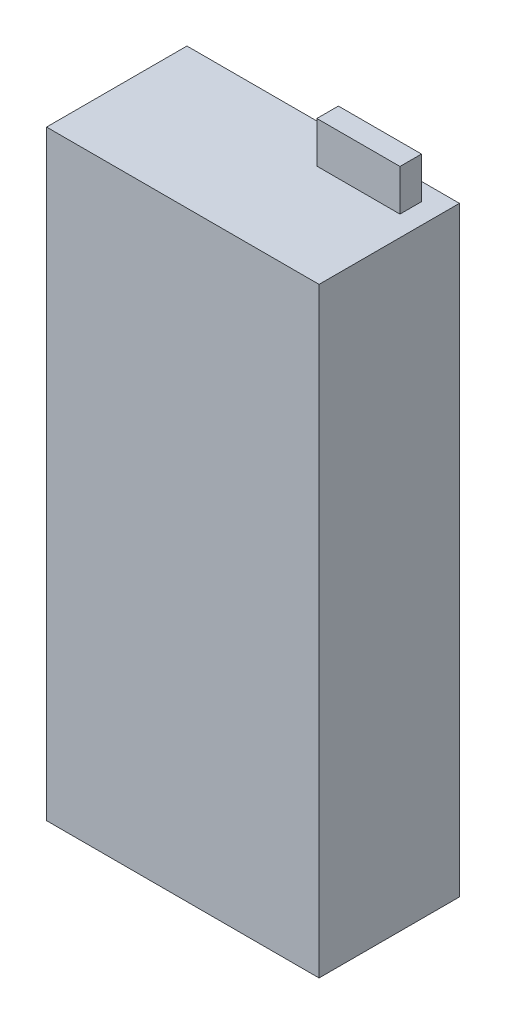
SolidWorks part; units mm, degrees
ref_plane "前视基准面" through (0, 0, 0) normal (0, 0, 1) x (1, 0, 0)
ref_plane "上视基准面" through (0, 0, 0) normal (0, 1, 0) x (1, 0, 0)
ref_plane "右视基准面" through (0, 0, 0) normal (1, 0, 0) x (0, 0, -1)
sketch "草图1" plane through (0, 0, 0) normal (0, 0, 1) x (1, 0, 0)
  line L1 (-193.0746, 287.1493) -> (-61.0746, 287.1493)
  line L2 (-193.0746, 287.1493) -> (-193.0746, -3.8507)
  line L3 (-193.0746, -3.8507) -> (-61.0746, -3.8507)
  line L4 (-61.0746, 287.1493) -> (-61.0746, -3.8507)
  line L5 (-193.0746, 287.1493) -> (-61.0746, -3.8507) construction
  line L6 (-193.0746, -3.8507) -> (-61.0746, 287.1493) construction
  point P0 (-127.0746, 141.6493)
  dimension "D1" = 132
  dimension "D2" = 291
extrude "凸台-拉伸1" add sketch "草图1" along normal blind 68
sketch "草图2" plane through (-193.0746, 0, 0) normal (-1, 0, 0) x (0, 0, 1)
  line L0 (34, -3.8507) -> (34, 287.1493) construction
  line L1 (68, -3.8507) -> (0, -3.8507) construction
  line L2 (68, 287.1493) -> (0, 287.1493) construction
  line L3 (17.5, 23.1493) -> (55.5, 23.1493) construction
  line L4 (55.5, 23.1493) -> (55.5, 33.1493) construction
  line L5 (55.5, 28.1493) -> (47.2032, 28.1493) construction
  line L6 (47.2032, 28.1493) -> (47.2032, 264.4493) construction
  line L7 (47.2032, 146.2993) -> (37.4688, 146.2993) construction
  line L8 (68, 287.1493) -> (68, -3.8507) construction
  line L9 (68, 287.1493) -> (0, 287.1493) construction
  line L10 (0, 287.1493) -> (0, -3.8507) construction
  circle A0 centre (17.5, 23.1493) radius 2
  circle A1 centre (55.5, 23.1493) radius 2
  circle A2 centre (55.5, 33.1493) radius 2
  circle A3 centre (17.5, 33.1493) radius 2
  circle A4 centre (17.5, 269.4493) radius 2
  circle A5 centre (17.5, 259.4493) radius 2
  circle A6 centre (55.5, 259.4493) radius 2
  circle A7 centre (55.5, 269.4493) radius 2
  dimension "D1" = 12.5
  dimension "D2" = 10
  dimension "D3" = 38
  dimension "D4" = 27
  dimension "D5" = 10
  dimension "D6" = 236.3
extrude "切除-拉伸1" cut sketch "草图2" against normal blind 4
sketch "草图3" plane through (0, -3.8507, 0) normal (0, -1, 0) x (1, 0, 0)
  line L1 (-178.5983, 24.2214) -> (-125.5451, 24.2214)
  line L2 (-178.5983, 24.2214) -> (-178.5983, 14.0192)
  line L3 (-178.5983, 14.0192) -> (-125.5451, 14.0192)
  line L4 (-125.5451, 24.2214) -> (-125.5451, 14.0192)
extrude "凸台-拉伸2" add sketch "草图3" along normal blind 20
sketch "草图4" plane through (0, -3.8507, 0) normal (0, -1, 0) x (1, 0, 0)
  circle A0 centre (-94.2519, 37.5872) radius 24.1206
extrude "凸台-拉伸3" add sketch "草图4" along normal blind 5
sketch "草图5" plane through (0, 287.1493, 0) normal (0, 1, 0) x (1, 0, 0)
  line L1 (-70.9484, -18.9316) -> (-111.2022, -18.9316)
  line L2 (-70.9484, -18.9316) -> (-70.9484, -8.5092)
  line L3 (-70.9484, -8.5092) -> (-111.2022, -8.5092)
  line L4 (-111.2022, -18.9316) -> (-111.2022, -8.5092)
extrude "凸台-拉伸4" add sketch "草图5" along normal blind 20
